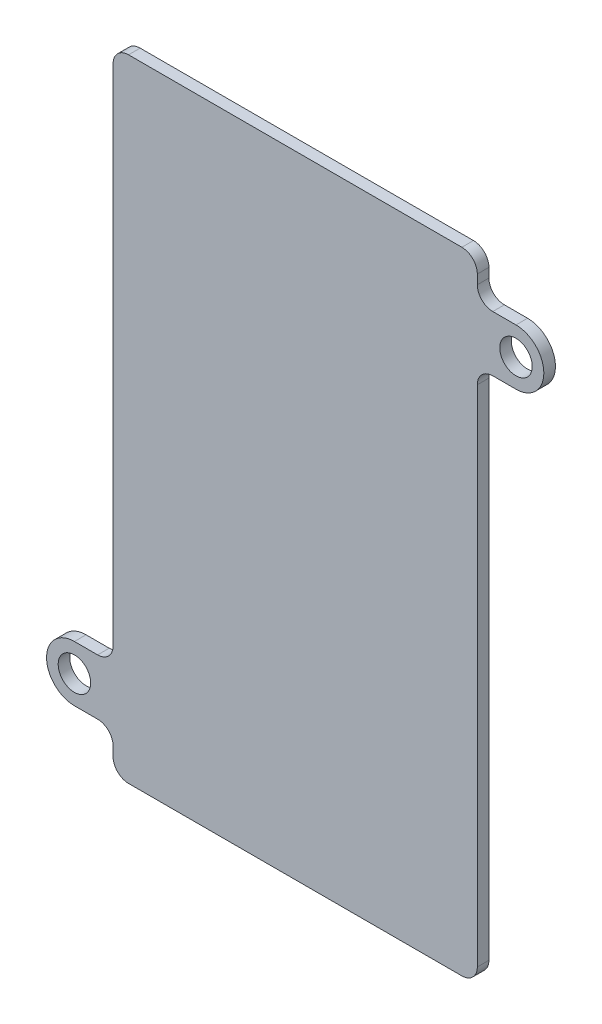
SolidWorks part; units mm, degrees
ref_plane "Front Plane" through (0, 0, 0) normal (0, 0, 1) x (1, 0, 0)
ref_plane "Top Plane" through (0, 0, 0) normal (0, 1, 0) x (1, 0, 0)
ref_plane "Right Plane" through (0, 0, 0) normal (1, 0, 0) x (0, 0, -1)
sketch "Sketch1" plane through (0, 0, 0) normal (0, 0, -1) x (-1, 0, 0)
  line L0 (-23.55, 40.8) -> (23.55, 40.8)
  line L5 (23.55, -40.8) -> (23.55, 40.8)
  line L6 (-23.55, -40.8) -> (23.55, -40.8)
  line L11 (-23.55, -40.8) -> (-23.55, 40.8)
  line L12 (-28.55, 32) -> (28.55, -32) construction
  line L13 (-28.55, 35.6) -> (-23.55, 35.6)
  line L14 (-20.55, -37.8) -> (20.55, -37.8)
  line L15 (-20.55, -37.8) -> (-20.55, 37.8)
  line L16 (-20.55, 37.8) -> (20.55, 37.8)
  line L17 (20.55, -37.8) -> (20.55, 37.8)
  line L18 (-20.55, -37.8) -> (20.55, 37.8) construction
  line L19 (-20.55, 37.8) -> (20.55, -37.8) construction
  line L20 (-28.55, 28.4) -> (-23.55, 28.4)
  line L21 (28.55, -35.6) -> (23.55, -35.6)
  line L22 (28.55, -28.4) -> (23.55, -28.4)
  line L24 (-5, 40.8) -> (5, 40.8)
  line L25 (-5, 40.8) -> (-5, 37.8)
  line L26 (-5, 37.8) -> (5, 37.8)
  line L27 (5, 40.8) -> (5, 37.8)
  circle A0 centre (28.55, -32) radius 2.1
  circle A1 centre (-28.55, 32) radius 2.1
  circle A2 centre (-28.55, 32) radius 3.6
  circle A3 centre (28.55, -32) radius 3.6
  point P0 (0, 0)
  point P11 (0, 0)
  point P25 (0, 37.8)
  point P30 (5.4034, -72.2)
  point P31 (5.4783, -69.2)
  point P32 (0, 0)
  dimension "D5" = 1.5
  dimension "D6" = 4.2
  dimension "D2" = 3
  dimension "D3" = 41.1
  dimension "D4" = 75.6
  dimension "D7" = 32
  dimension "D8" = 5
  dimension "D9" = 10
extrude "Boss-Extrude1" add sketch "Sketch1" along normal blind 1.5 contours L22 A3 L21 L5 | L27 L0 L5 L6 L11 L25 L16 L15 L14 L17 | A2 A1 | L20 A2 L13 L11 | L17 L14 L15 L16 | L0 L27 L16 L25 | A0
fillet "Fillet1" radius 2 8 edges at (23.55, 28.4, -0.75) (-23.55, -28.4, -0.75) (23.55, 35.6, -0.75) (23.55, 40.8, -0.75) (-23.55, 40.8, -0.75) (23.55, -40.8, -0.75) (-23.55, -40.8, -0.75) (-23.55, -35.6, -0.75)
